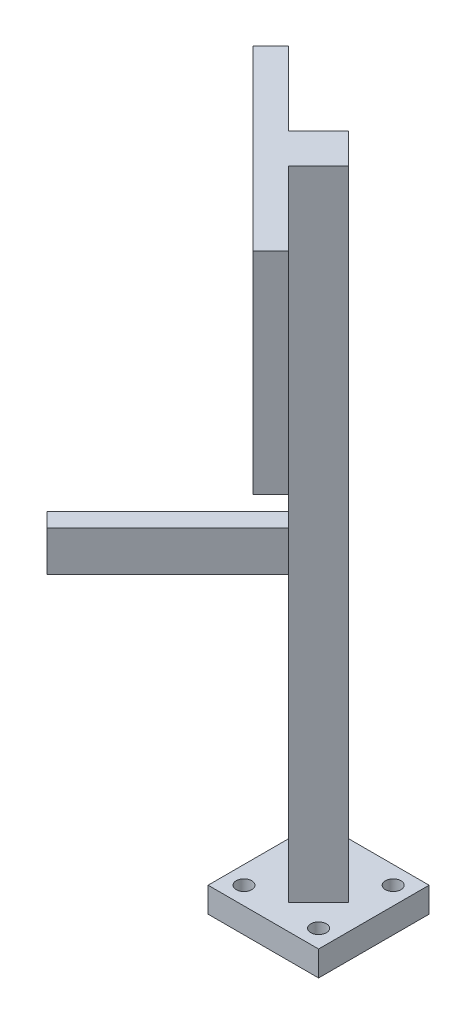
SolidWorks part; units mm, degrees
ref_plane "前视基准面" through (0, 0, 0) normal (0, 0, 1) x (1, 0, 0)
ref_plane "上视基准面" through (0, 0, 0) normal (0, 1, 0) x (1, 0, 0)
ref_plane "右视基准面" through (0, 0, 0) normal (1, 0, 0) x (0, 0, -1)
sketch "草图1" plane through (0, 0, 0) normal (0, 1, 0) x (1, 0, 0)
  line L1 (-11, 11) -> (11, 11)
  line L2 (-11, 11) -> (-11, -11)
  line L3 (-11, -11) -> (11, -11)
  line L4 (11, 11) -> (11, -11)
  line L5 (-11, 11) -> (11, -11) construction
  line L6 (-11, -11) -> (11, 11) construction
  circle A0 centre (-7.4246, 7.4246) radius 1.55
  circle A1 centre (7.4246, 7.4246) radius 1.55
  circle A2 centre (7.4246, -7.4246) radius 1.55
  circle A3 centre (-7.4246, -7.4246) radius 1.55
  point P0 (0, 0)
  point P6 (-7.4246, 7.4246)
  point P18 (0, 0)
  dimension "D4" = 3.1
  dimension "D1" = 22
  dimension "D2" = 22
  dimension "D3" = 10.5
  dimension "D5" = 4
extrude "凸台-拉伸1" add sketch "草图1" along normal blind 5
ref_plane "基准面2" through (0, 5, 0) normal (0, 1, 0) x (1, 0, 0)
sketch "草图2" plane through (0, 5, 0) normal (0, 1, 0) x (1, 0, 0)
  line L0 (0, 0) -> (35355.3391, -35355.3391) construction
  line L1 (0, 0) -> (-35355.3391, -35355.3391) construction
  line L2 (0, 6) -> (-6, 0)
  line L3 (-6, 0) -> (0, -6)
  line L4 (0, -6) -> (6, 0)
  line L5 (6, 0) -> (0, 6)
  point P7 (0, 6)
  point P11 (6, 0)
  point P12 (0, -6)
  point P13 (-6, 0)
  point P14 (0, 0)
  dimension "D2" = 6
  dimension "D1" = 4
extrude "凸台-拉伸2" add sketch "草图2" along normal blind 127
ref_plane "基准面3" through (-3, 0, 3) normal (-0.7071, 0, 0.7071) x (0.7071, 0, 0.7071)
sketch "草图3" plane through (-3, 0, 3) normal (-0.7071, 0, 0.7071) x (0.7071, 0, 0.7071)
  line L0 (0, 0) -> (15.5563, 0) construction
  line L1 (0, 132) -> (0, -49868) construction
  line L2 (-4.2426, 132) -> (4.2426, 132) construction
  line L3 (-15.5563, 0) -> (0, 0) construction
  line L4 (-2, 68) -> (2, 68)
  line L5 (2, 68) -> (2, 60)
  line L6 (2, 60) -> (-2, 60)
  line L7 (-2, 60) -> (-2, 68)
  point P0 (-2, 60)
  point P1 (2, 60)
  point P6 (0, 132)
  point P9 (-2, 68)
  point P10 (2, 68)
  dimension "D1" = 4
  dimension "D2" = 60
  dimension "D3" = 68
  dimension "D4" = 68
extrude "凸台-拉伸3" add sketch "草图3" along normal blind 34
sketch "草图4" plane through (-3, 0, 3) normal (-0.7071, 0, 0.7071) x (0.7071, 0, 0.7071)
  line L1 (0, 0) -> (15.5563, 0) construction
  line L2 (0, 132) -> (0, -49868) construction
  line L3 (-4.2426, 132) -> (4.2426, 132) construction
  line L4 (4.2426, 132) -> (25, 132)
  line L5 (25, 132) -> (25, 90)
  line L6 (25, 90) -> (-25, 90)
  line L7 (-25, 90) -> (-25, 132)
  line L8 (-25, 132) -> (4.2426, 132)
  point P10 (0, 132)
  point P13 (25, 90)
  point P14 (-25, 90)
  dimension "D3" = 50
  dimension "D4" = 90
extrude "凸台-拉伸4" add sketch "草图4" along normal blind 5
ref_plane "基准面4" through (-6.5355, 0, 6.5355) normal (-0.7071, 0, 0.7071) x (0.7071, 0, 0.7071)
sketch "草图7" plane through (-6.5355, 0, 6.5355) normal (-0.7071, 0, 0.7071) x (0.7071, 0, 0.7071)
  line L0 (-25, 90) -> (25, 90) construction
  line L1 (0, 94) -> (0, 50094) construction
  line L2 (-4.2426, 90) -> (4.2426, 90) construction
  line L4 (25, 132) -> (-25, 132) construction
  line L12 (-16.28, 91) -> (-16.28, 131)
  line L13 (-16.28, 131) -> (-13.18, 131)
  line L14 (-13.18, 131) -> (-13.18, 91)
  line L15 (-13.18, 91) -> (-16.28, 91)
  line L16 (13.18, 91) -> (13.18, 131)
  line L17 (13.18, 131) -> (16.28, 131)
  line L18 (16.28, 131) -> (16.28, 91)
  line L19 (16.28, 91) -> (13.18, 91)
  point P0 (-14.73, 90)
  point P7 (0, 90)
  point P8 (14.73, 90)
  point P9 (-13.18, 90)
  point P10 (-16.28, 90)
  point P11 (13.18, 90)
  point P12 (16.28, 90)
  dimension "D1" = 29.46
  dimension "D2" = 1.55
  dimension "D3" = 1.55
  dimension "D4" = 1.55
  dimension "D5" = 1.55
  dimension "D6" = 1
  dimension "D7" = 1
  dimension "D8" = 1
  dimension "D9" = 1
extrude "切除-拉伸3" cut sketch "草图7" against normal blind 5
